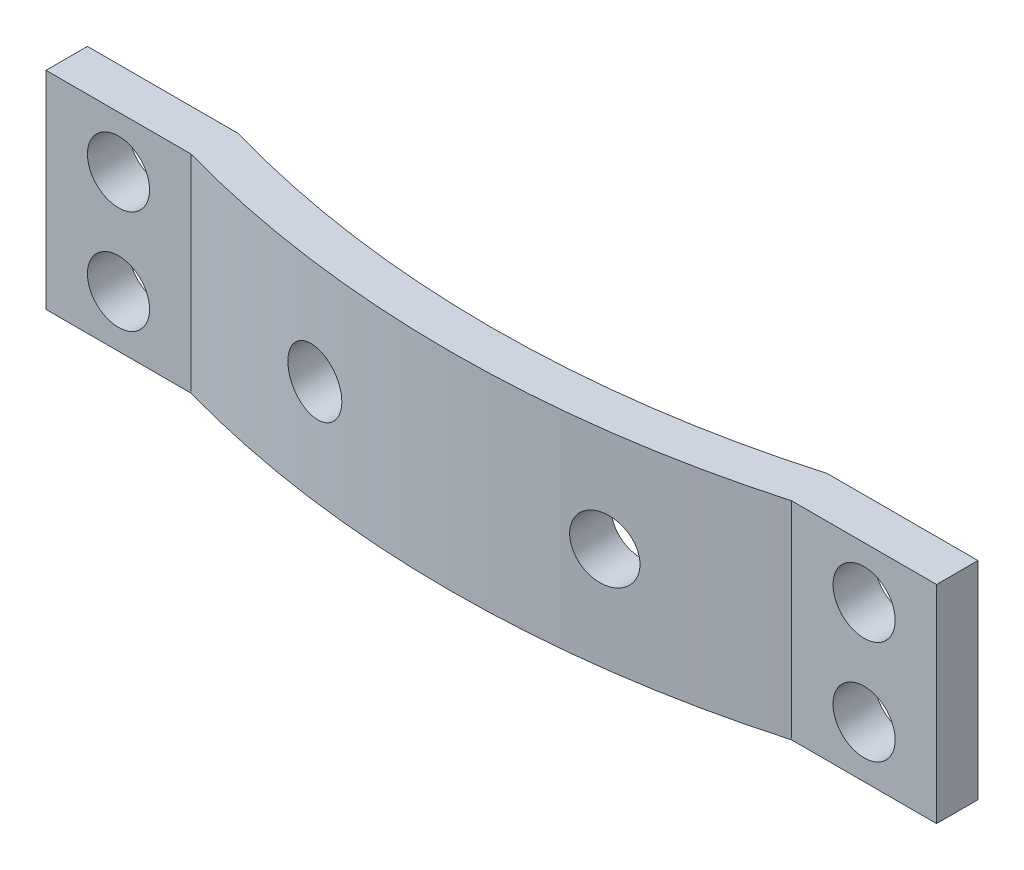
SolidWorks part; units mm, degrees
ref_plane "Спереди" through (0, 0, 0) normal (0, 0, 1) x (1, 0, 0)
ref_plane "Сверху" through (0, 0, 0) normal (0, 1, 0) x (1, 0, 0)
ref_plane "Справа" through (0, 0, 0) normal (1, 0, 0) x (0, 0, -1)
sketch "Эскиз1" plane through (0, 0, 0) normal (0, 1, 0) x (1, 0, 0)
  line L0 (0, 0) -> (-7, 0)
  line L1 (-36, 0) -> (-43, 0)
  arc A0 (-7, 0) -> (-36, 0) centre (-21.5, 51.5625) cw
  point P8 (-21.5, -2)
  dimension "D1" = 43
  dimension "D4" = 2
  dimension "D2" = 7
  dimension "D3" = 7
extrude "Вытянуть-Тонкостенный1" add sketch "Эскиз1" along normal blind 10 thin
sketch "Эскиз2" plane through (0, 0, 0) normal (0, 0, 1) x (1, 0, 0)
  line L0 (-43, 10) -> (-36, 0) construction
  line L1 (-36, 10) -> (-43, 0) construction
  line L2 (-39.5, 5) -> (-39.5, 10) construction
  line L3 (-36, 10) -> (-43, 10) construction
  line L4 (-39.5, 5) -> (-39.5, 0) construction
  line L5 (-36, 0) -> (-43, 0) construction
  line L6 (0, 10) -> (-7, 0) construction
  line L7 (-7, 10) -> (0, 0) construction
  line L8 (-3.5, 10) -> (-3.5, 5) construction
  line L11 (0, 10) -> (-7, 10) construction
  line L12 (-3.5, 5) -> (-3.5, 0) construction
  line L13 (0, 0) -> (-7, 0) construction
  circle A0 centre (-39.5, 7.5) radius 1.5
  circle A1 centre (-39.5, 2.5) radius 1.5
  circle A2 centre (-3.5, 7.5) radius 1.5
  circle A3 centre (-3.5, 2.5) radius 1.5
extrude "Вырез-Вытянуть1" cut sketch "Эскиз2" against normal blind 2
ref_plane "Плоскость2" through (0, 0, 2) normal (0, 0, 1) x (1, 0, 0)
sketch "Эскиз4" plane through (0, 0, 2) normal (0, 0, 1) x (1, 0, 0)
  line L0 (-21.5, 10) -> (-21.5, 0) construction
  line L1 (-7, 10) -> (-36, 10) construction
  line L2 (-36, 0) -> (-7, 0) construction
  line L3 (-36, 5) -> (-7, 5) construction
  line L4 (-36, 10) -> (-36, 0) construction
  line L5 (-7, 10) -> (-7, 0) construction
  line L6 (-28.5, 10) -> (-28.5, 0) construction
  line L7 (-14.5, 10) -> (-14.5, 0) construction
  circle A0 centre (-28.5, 5) radius 1.5
  circle A1 centre (-14.5, 5) radius 1.5
  dimension "D3" = 5
  dimension "D1" = 7
  dimension "D2" = 7
extrude "Вырез-Вытянуть3" cut sketch "Эскиз4" against normal blind 3
